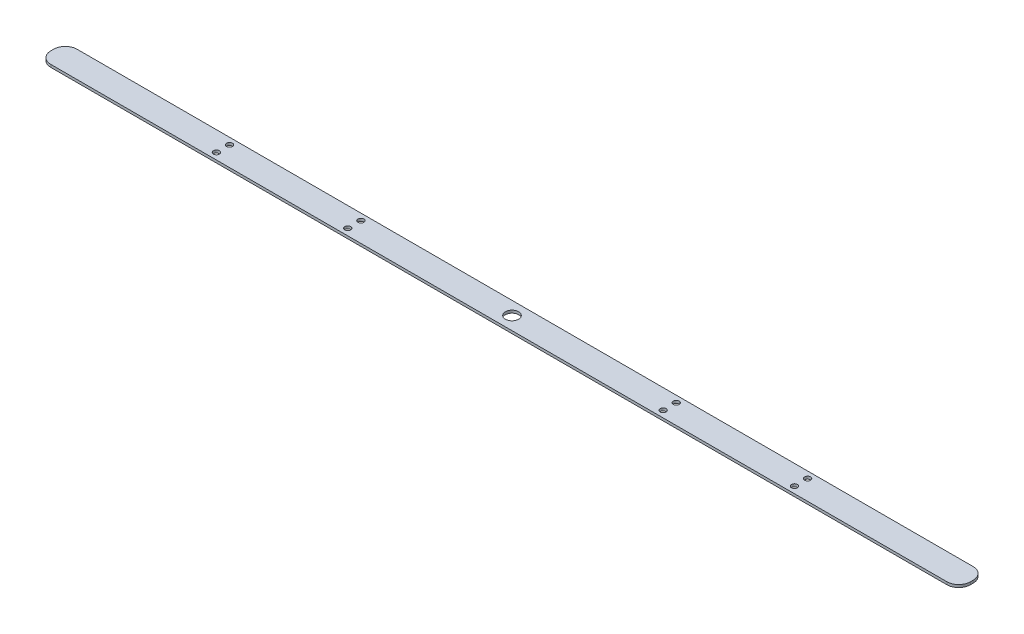
SolidWorks part; units mm, degrees
ref_plane "Front Plane" through (0, 0, 0) normal (0, 0, 1) x (1, 0, 0)
ref_plane "Top Plane" through (0, 0, 0) normal (0, 1, 0) x (1, 0, 0)
ref_plane "Right Plane" through (0, 0, 0) normal (1, 0, 0) x (0, 0, -1)
sketch "Sketch1" plane through (0, 0, 0) normal (0, 1, 0) x (1, 0, 0)
  line L1 (0, 0) -> (700, 0)
  line L2 (0, 0) -> (0, 20)
  line L3 (0, 20) -> (700, 20)
  line L4 (700, 0) -> (700, 20)
  dimension "D1" = 700
  dimension "D2" = 20
extrude "Boss-Extrude1" add sketch "Sketch1" along normal blind 2
fillet "Fillet1" radius 9 4 edges at (0, 1, 0) (0, 1, -20) (700, 1, -20) (700, 1, 0)
sketch "Sketch2" plane through (0, 2, 0) normal (0, 1, 0) x (1, 0, 0)
  line L0 (350, 20) -> (350, 0) construction
  line L1 (691, 20) -> (9, 20) construction
  line L2 (9, 0) -> (691, 0) construction
  line L3 (0, 10) -> (350, 10) construction
  line L4 (0, 11) -> (0, 9) construction
  circle A0 centre (350, 10) radius 5
  circle A1 centre (130, 15) radius 2.25
  circle A2 centre (230, 15) radius 2.25
  circle A3 centre (130, 5) radius 2.25
  circle A5 centre (230, 5) radius 2.25
  circle A6 centre (470, 15) radius 2.25
  circle A7 centre (470, 5) radius 2.25
  circle A8 centre (570, 5) radius 2.25
  circle A9 centre (570, 15) radius 2.25
  point P14 (0, 0)
  point P17 (127.3743, 15)
  dimension "D1" = 10
  dimension "D2" = 4.5
  dimension "D3" = 100
  dimension "D4" = 10
  dimension "D5" = 120
extrude "Cut-Extrude1" cut sketch "Sketch2" against normal through all
